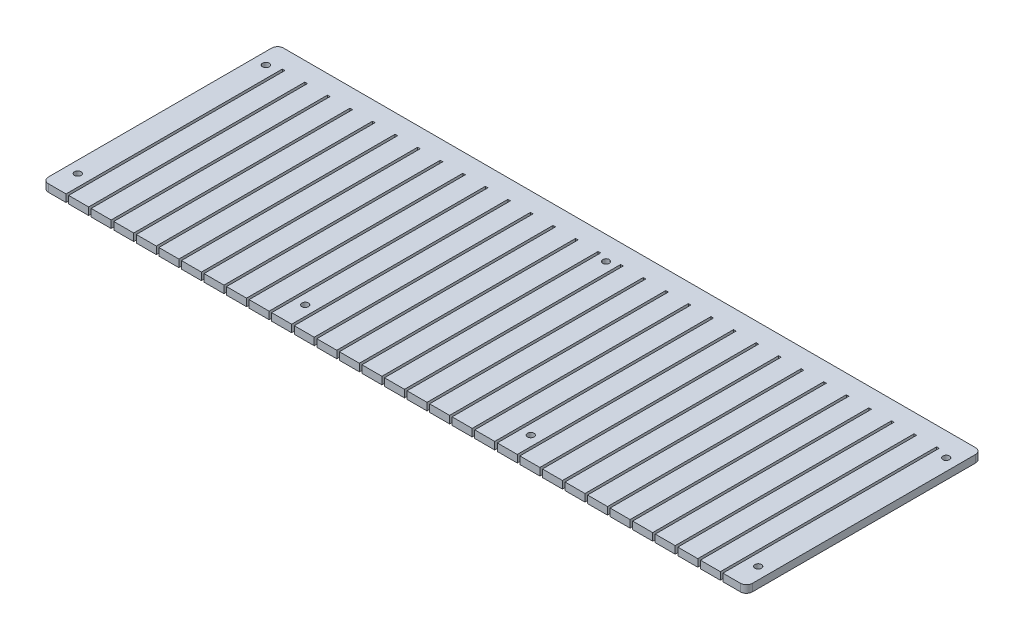
SolidWorks part; units mm, degrees
material "Acrylic (Medium-high impact)"
ref_plane "Front Plane" through (0, 0, 0) normal (0, 0, 1) x (1, 0, 0)
ref_plane "Top Plane" through (0, 0, 0) normal (0, 1, 0) x (1, 0, 0)
ref_plane "Right Plane" through (0, 0, 0) normal (1, 0, 0) x (0, 0, -1)
sketch "Sketch3" plane through (0, 0, 0) normal (0, 1, 0) x (1, 0, 0)
  line L0 (-71.45, 42) -> (-71.45, -50)
  line L1 (-139.75, 42) -> (-138.65, 42)
  line L2 (-139.75, 42) -> (-139.75, -50)
  line L3 (-139.75, -50) -> (-138.65, -50)
  line L4 (-138.65, 42) -> (-138.65, -50)
  line L5 (0, 50) -> (0, -50) construction
  line L6 (-129.05, 42) -> (-129.05, -50)
  line L7 (-130.15, 42) -> (-130.15, -50)
  line L8 (-130.15, -50) -> (-129.05, -50)
  line L9 (-130.15, 42) -> (-129.05, 42)
  line L10 (-119.45, 42) -> (-119.45, -50)
  line L11 (-120.55, 42) -> (-120.55, -50)
  line L12 (-120.55, -50) -> (-119.45, -50)
  line L13 (-120.55, 42) -> (-119.45, 42)
  line L14 (-109.85, 42) -> (-109.85, -50)
  line L15 (-110.95, 42) -> (-110.95, -50)
  line L16 (-110.95, -50) -> (-109.85, -50)
  line L17 (-110.95, 42) -> (-109.85, 42)
  line L18 (-100.25, 42) -> (-100.25, -50)
  line L19 (-101.35, 42) -> (-101.35, -50)
  line L20 (-101.35, -50) -> (-100.25, -50)
  line L21 (-101.35, 42) -> (-100.25, 42)
  line L22 (-90.65, 42) -> (-90.65, -50)
  line L23 (-91.75, 42) -> (-91.75, -50)
  line L24 (-91.75, -50) -> (-90.65, -50)
  line L25 (-91.75, 42) -> (-90.65, 42)
  line L26 (-81.05, 42) -> (-81.05, -50)
  line L27 (-82.15, 42) -> (-82.15, -50)
  line L28 (-82.15, -50) -> (-81.05, -50)
  line L29 (-82.15, 42) -> (-81.05, 42)
  line L30 (-72.55, 42) -> (-72.55, -50)
  line L31 (-72.55, -50) -> (-71.45, -50)
  line L32 (-72.55, 42) -> (-71.45, 42)
  line L33 (-61.85, 42) -> (-61.85, -50)
  line L34 (-62.95, 42) -> (-62.95, -50)
  line L35 (-62.95, -50) -> (-61.85, -50)
  line L36 (-62.95, 42) -> (-61.85, 42)
  line L37 (-52.25, 42) -> (-52.25, -50)
  line L38 (-53.35, 42) -> (-53.35, -50)
  line L39 (-53.35, -50) -> (-52.25, -50)
  line L40 (-53.35, 42) -> (-52.25, 42)
  line L41 (-42.65, 42) -> (-42.65, -50)
  line L42 (-43.75, 42) -> (-43.75, -50)
  line L43 (-43.75, -50) -> (-42.65, -50)
  line L44 (-147.25, 50) -> (147.25, 50)
  line L45 (-149.75, 47.5) -> (-149.75, -47.5)
  line L46 (-147.25, -50) -> (147.25, -50)
  line L47 (149.75, 47.5) -> (149.75, -47.5)
  line L48 (-43.75, 42) -> (-42.65, 42)
  line L49 (-33.05, 42) -> (-33.05, -50)
  line L50 (-34.15, 42) -> (-34.15, -50)
  line L51 (-34.15, -50) -> (-33.05, -50)
  line L52 (-34.15, 42) -> (-33.05, 42)
  line L53 (-23.45, 42) -> (-23.45, -50)
  line L54 (-24.55, 42) -> (-24.55, -50)
  line L55 (-24.55, -50) -> (-23.45, -50)
  line L56 (-24.55, 42) -> (-23.45, 42)
  line L57 (-13.85, 42) -> (-13.85, -50)
  line L58 (-14.95, 42) -> (-14.95, -50)
  line L59 (-14.95, -50) -> (-13.85, -50)
  line L60 (-14.95, 42) -> (-13.85, 42)
  line L61 (-4.25, 42) -> (-4.25, -50)
  line L62 (-5.35, 42) -> (-5.35, -50)
  line L63 (-5.35, -50) -> (-4.25, -50)
  line L64 (-5.35, 42) -> (-4.25, 42)
  line L65 (5.35, 42) -> (5.35, -50)
  line L66 (4.25, 42) -> (4.25, -50)
  line L67 (4.25, -50) -> (5.35, -50)
  line L68 (4.25, 42) -> (5.35, 42)
  line L69 (14.95, 42) -> (14.95, -50)
  line L70 (13.85, 42) -> (13.85, -50)
  line L71 (13.85, -50) -> (14.95, -50)
  line L72 (13.85, 42) -> (14.95, 42)
  line L73 (24.55, 42) -> (24.55, -50)
  line L74 (23.45, 42) -> (23.45, -50)
  line L75 (23.45, -50) -> (24.55, -50)
  line L76 (23.45, 42) -> (24.55, 42)
  line L77 (34.15, 42) -> (34.15, -50)
  line L78 (33.05, 42) -> (33.05, -50)
  line L79 (33.05, -50) -> (34.15, -50)
  line L80 (33.05, 42) -> (34.15, 42)
  line L81 (43.75, 42) -> (43.75, -50)
  line L82 (42.65, 42) -> (42.65, -50)
  line L83 (42.65, -50) -> (43.75, -50)
  line L84 (42.65, 42) -> (43.75, 42)
  line L85 (53.35, 42) -> (53.35, -50)
  line L86 (52.25, 42) -> (52.25, -50)
  line L87 (52.25, -50) -> (53.35, -50)
  line L88 (52.25, 42) -> (53.35, 42)
  line L89 (62.95, 42) -> (62.95, -50)
  line L90 (61.85, 42) -> (61.85, -50)
  line L91 (61.85, -50) -> (62.95, -50)
  line L92 (61.85, 42) -> (62.95, 42)
  line L93 (72.55, 42) -> (72.55, -50)
  line L94 (71.45, 42) -> (71.45, -50)
  line L95 (71.45, -50) -> (72.55, -50)
  line L96 (71.45, 42) -> (72.55, 42)
  line L97 (82.15, 42) -> (82.15, -50)
  line L98 (81.05, 42) -> (81.05, -50)
  line L99 (81.05, -50) -> (82.15, -50)
  line L100 (81.05, 42) -> (82.15, 42)
  line L101 (91.75, 42) -> (91.75, -50)
  line L102 (90.65, 42) -> (90.65, -50)
  line L103 (90.65, -50) -> (91.75, -50)
  line L104 (90.65, 42) -> (91.75, 42)
  line L105 (101.35, 42) -> (101.35, -50)
  line L106 (100.25, 42) -> (100.25, -50)
  line L107 (100.25, -50) -> (101.35, -50)
  line L108 (100.25, 42) -> (101.35, 42)
  line L109 (110.95, 42) -> (110.95, -50)
  line L110 (109.85, 42) -> (109.85, -50)
  line L111 (109.85, -50) -> (110.95, -50)
  line L112 (109.85, 42) -> (110.95, 42)
  line L113 (120.55, 42) -> (120.55, -50)
  line L114 (119.45, 42) -> (119.45, -50)
  line L115 (119.45, -50) -> (120.55, -50)
  line L116 (119.45, 42) -> (120.55, 42)
  line L117 (130.15, 42) -> (130.15, -50)
  line L118 (129.05, 42) -> (129.05, -50)
  line L119 (129.05, -50) -> (130.15, -50)
  line L120 (129.05, 42) -> (130.15, 42)
  line L121 (139.75, 42) -> (139.75, -50)
  line L122 (138.65, 42) -> (138.65, -50)
  line L123 (138.65, -50) -> (139.75, -50)
  line L124 (138.65, 42) -> (139.75, 42)
  line L125 (139.75, 42) -> (-139.75, 42) construction
  line L126 (-52.25, -40) -> (-43.75, -40) construction
  line L127 (43.75, -40) -> (52.25, -40) construction
  circle A0 centre (-144.75, 40) radius 1.4
  circle A1 centre (-144.75, -40) radius 1.4
  circle A2 centre (144.75, -40) radius 1.4
  circle A3 centre (144.75, 40) radius 1.4
  arc A4 (147.25, -50) -> (149.75, -47.5) centre (147.25, -47.5) ccw
  arc A5 (-149.75, -47.5) -> (-147.25, -50) centre (-147.25, -47.5) ccw
  arc A6 (147.25, 50) -> (149.75, 47.5) centre (147.25, 47.5) cw
  arc A7 (-147.25, 50) -> (-149.75, 47.5) centre (-147.25, 47.5) ccw
  circle A8 centre (-48, -40) radius 1.4
  circle A9 centre (48, -40) radius 1.4
  circle A10 centre (0, 40) radius 1.4
  point P33 (0, 42)
  dimension "D7" = 10
  dimension "D8" = 5
  dimension "D9" = 90
  dimension "D10" = 5
  dimension "D6" = 2.8
  dimension "D11" = 2.5
  dimension "D12" = 10
  dimension "D2" = 1.1
  dimension "D3" = 8
  dimension "D5" = 8.5
  dimension "D4" = 30
extrude "Boss-Extrude1" add sketch "Sketch3" along normal blind 3.175 contours L44 A7 L45 A5 L46 L2 L1 L4 L7 L9 L6 L11 L13 L10 L15 L17 L14 L19 L21 L18 L23 L25 L22 L27 L29 L26 L30 L32 L0 L34 L36 L33 L38 L40 L37 L42 L48 L41 L50 L52
